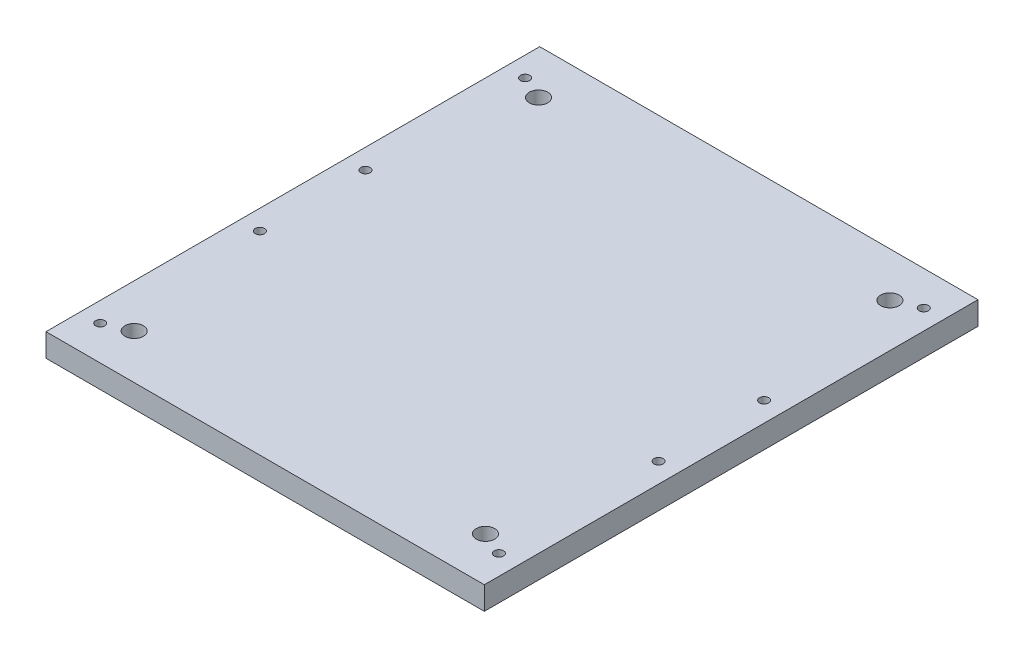
SolidWorks part; units mm, degrees
ref_plane "Front Plane" through (0, 0, 0) normal (0, 0, 1) x (1, 0, 0)
ref_plane "Top Plane" through (0, 0, 0) normal (0, 1, 0) x (1, 0, 0)
ref_plane "Right Plane" through (0, 0, 0) normal (1, 0, 0) x (0, 0, -1)
sketch "Sketch2" plane through (0, 0, 0) normal (0, 1, 0) x (1, 0, 0)
  line L0 (38.075, -43.825) -> (47.5, -43.825)
  line L1 (-47.5, -53.5) -> (47.5, -53.5)
  line L2 (-47.5, -53.5) -> (-47.5, 53.5)
  line L3 (-47.5, 53.5) -> (47.5, 53.5)
  line L4 (47.5, -53.5) -> (47.5, 53.5)
  line L5 (-47.5, -53.5) -> (47.5, 53.5) construction
  line L6 (-47.5, 53.5) -> (47.5, -53.5) construction
  line L7 (38.075, -43.825) -> (38.075, -53.5)
  line L8 (-55, 0) -> (55, 0) construction
  line L9 (0, -55) -> (0, 55) construction
  line L15 (-60, 66) -> (60, 66)
  line L16 (-60, 66) -> (-60, -66)
  line L17 (-60, -66) -> (60, -66)
  line L18 (60, 66) -> (60, -66)
  line L19 (-60, 66) -> (60, -66) construction
  line L20 (-60, -66) -> (60, 66) construction
  circle A1 centre (38.075, -43.825) radius 2
  circle A2 centre (38.075, 43.825) radius 2
  circle A3 centre (-38.075, -43.825) radius 2
  circle A4 centre (-38.075, 43.825) radius 2
  point P0 (0, 0)
  point P20 (0, 0)
  point P21 (0, 0)
  dimension "D3" = 76.15
  dimension "D5" = 4
  dimension "D4" = 87.65
  dimension "D1" = 95
  dimension "D2" = 107
  dimension "D6" = 120
  dimension "D7" = 132
extrude "Boss-Extrude1" add sketch "Sketch2" along normal blind 5 contours A1 L0 L4 L3 L2 L1 L7 A4 A2 A3 | A1 L7 L1 L4 L0
sketch "Sketch3" plane through (0, 5, 0) normal (0, 1, 0) x (1, 0, 0)
  line L5 (-47.515, 40.2371) -> (-32.4121, 40.2371) construction
  line L6 (-47.5, -53.5) -> (-47.5, 53.5) construction
  line L10 (-47.5, 17.2402) -> (-47.5, 40.2371)
  line L11 (-47.6, 40.3371) -> (-32.2822, 40.3371)
  line L12 (-32.2822, 40.3371) -> (-30.49, 37.2328)
  line L13 (-30.49, 17.1402) -> (-30.49, 37.2328)
  line L14 (-47.6, 17.1402) -> (-30.49, 17.1402)
  line L15 (-47.6, 17.1402) -> (-47.6, 40.3371)
  line L16 (-47.5, 40.2371) -> (-32.34, 40.2371) construction
  line L17 (-47.5, 17.2402) -> (-30.59, 17.2402) construction
  line L18 (-30.59, 17.2402) -> (-30.59, 37.206) construction
  line L19 (-32.34, 40.2371) -> (-30.59, 37.206) construction
  line L20 (0, 62.7045) -> (0, 59.4045) construction
  line L21 (32.2822, 40.3371) -> (30.49, 37.2328)
  line L22 (30.49, 17.1402) -> (30.49, 37.2328)
  line L23 (47.6, 17.1402) -> (30.49, 17.1402)
  line L24 (47.5, 17.2402) -> (47.5, 40.2371)
  line L25 (47.6, 40.3371) -> (32.2822, 40.3371)
  line L26 (-130.0965, 0) -> (-126.7965, 0) construction
  line L27 (47.5, -17.2402) -> (47.5, -40.2371)
  line L28 (47.6, -17.1402) -> (30.49, -17.1402)
  line L29 (30.49, -17.1402) -> (30.49, -37.2328)
  line L30 (32.2822, -40.3371) -> (30.49, -37.2328)
  line L31 (47.6, -40.3371) -> (32.2822, -40.3371)
  line L32 (-30.49, -17.1402) -> (-30.49, -37.2328)
  line L33 (-32.2822, -40.3371) -> (-30.49, -37.2328)
  line L34 (-47.6, -40.3371) -> (-32.2822, -40.3371)
  line L35 (-47.5, -17.2402) -> (-47.5, -40.2371)
  line L36 (-47.6, -17.1402) -> (-30.49, -17.1402)
  dimension "D1" = 0.1
sketch "Sketch4" plane through (0, 5, 0) normal (0, 1, 0) x (1, 0, 0)
  line L0 (-47.5, 53.5) -> (47.5, 53.5) construction
  circle A0 centre (43.205, 46.04) radius 1
  circle A1 centre (38.075, 43.825) radius 2 construction
  dimension "D1" = 2
  dimension "D2" = 7.46
  dimension "D3" = 5.13
sketch "Sketch6" plane through (0, 5, 0) normal (0, 1, 0) x (1, 0, 0)
  line L0 (32.2822, 40.3371) -> (32.2822, 17.1402)
  line L1 (47.6, 17.1402) -> (30.49, 17.1402) construction
  line L2 (18.8792, 40.3371) -> (18.8792, 17.1402)
  line L3 (18.8792, 28.7386) -> (32.2822, 28.7386)
ref_plane "Plane1" through (0, 0, -28.7386) normal (0, 0, -1) x (-1, 0, 0)
extrude "Cut-Extrude1" cut sketch "Sketch4" against normal up to next
mirror "Mirror1" about plane through (0, 0, -28.7386) normal (0, 0, -1) of "Cut-Extrude1"
mirror "Mirror2" about plane through (0, 0, 0) normal (1, 0, 0) of "Mirror1", "Cut-Extrude1" second plane through (0, 0, 0) second plane normal (0, 0, 1)
